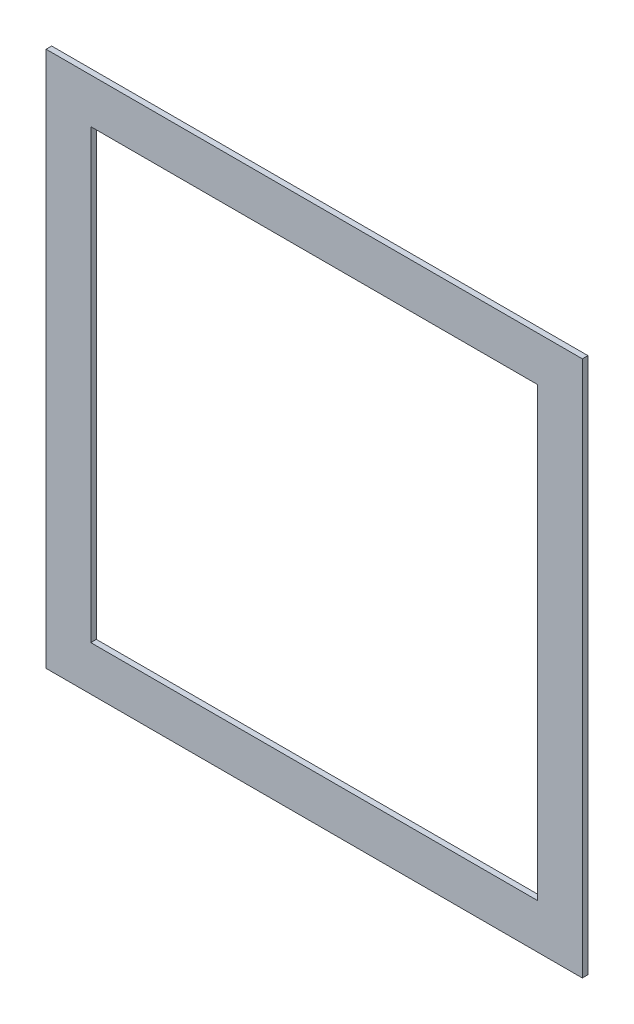
SolidWorks part; units mm, degrees
ref_plane "Front Plane" through (0, 0, 0) normal (0, 0, 1) x (1, 0, 0)
ref_plane "Top Plane" through (0, 0, 0) normal (0, 1, 0) x (1, 0, 0)
ref_plane "Right Plane" through (0, 0, 0) normal (1, 0, 0) x (0, 0, -1)
sketch "Sketch1" plane through (0, 0, 0) normal (0, 0, 1) x (1, 0, 0)
  line L1 (-69.0767, 47.3734) -> (83.3233, 47.3734)
  line L2 (-69.0767, 47.3734) -> (-69.0767, -105.0266)
  line L3 (-69.0767, -105.0266) -> (83.3233, -105.0266)
  line L4 (83.3233, 47.3734) -> (83.3233, -105.0266)
  line L5 (-56.3767, 34.6734) -> (70.6233, 34.6734)
  line L6 (-56.3767, 34.6734) -> (-56.3767, -92.3266)
  line L7 (-56.3767, -92.3266) -> (70.6233, -92.3266)
  line L8 (70.6233, 34.6734) -> (70.6233, -92.3266)
  dimension "D1" = 152.4
  dimension "D2" = 152.4
  dimension "D3" = 12.7
  dimension "D4" = 127
  dimension "D5" = 12.7
  dimension "D6" = 127
extrude "Boss-Extrude1" add sketch "Sketch1" along normal blind 1.5875
